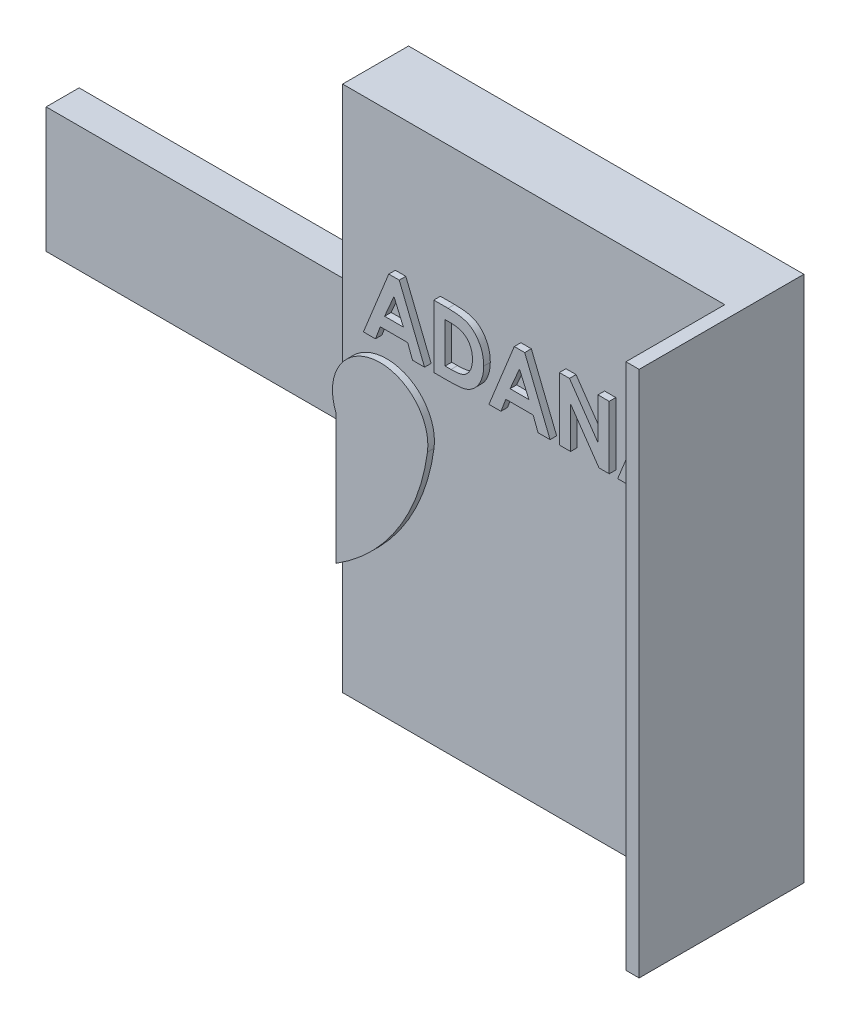
SolidWorks part; units mm, degrees
ref_plane "Ön Düzlem" through (0, 0, 0) normal (0, 0, 1) x (1, 0, 0)
ref_plane "Üst Düzlem" through (0, 0, 0) normal (0, 1, 0) x (1, 0, 0)
ref_plane "Sağ Düzlem" through (0, 0, 0) normal (1, 0, 0) x (0, 0, -1)
sketch "Çizim1" plane through (0, 0, 0) normal (0, 0, 1) x (1, 0, 0)
  line L1 (-30, 40) -> (30, 40)
  line L2 (-30, 40) -> (-30, -40)
  line L3 (-30, -40) -> (30, -40)
  line L4 (30, 40) -> (30, -40)
  line L5 (-30, 40) -> (30, -40) construction
  line L6 (-30, -40) -> (30, 40) construction
  point P0 (0, 0)
  dimension "D1" = 80
  dimension "D2" = 60
extrude "Yükseklik-Ekstrüzyon1" add sketch "Çizim1" along normal blind 10
ref_plane "Düzlem1" through (-30, 0, 0) normal (1, 0, 0) x (0, 0, -1)
sketch "Çizim2" plane through (-30, 0, 0) normal (1, 0, 0) x (0, 0, -1)
  line L0 (0, 40) -> (0, -40) construction
  line L1 (-5, 9.5) -> (0, 9.5)
  line L2 (-5, 9.5) -> (-5, -9.5)
  line L3 (-5, -9.5) -> (0, -9.5)
  line L4 (0, 9.5) -> (0, -9.5)
  line L5 (-5, 9.5) -> (0, -9.5) construction
  line L6 (-5, -9.5) -> (0, 9.5) construction
  point P0 (-2.5, 0)
  dimension "D1" = 5
  dimension "D2" = 19
extrude "Yükseklik-Ekstrüzyon2" add sketch "Çizim2" against normal blind 50
ref_plane "Düzlem2" through (30, 0, 0) normal (1, 0, 0) x (0, 0, -1)
sketch "Çizim3" plane through (30, 0, 0) normal (1, 0, 0) x (0, 0, -1)
  line L0 (-10, -40) -> (-10, 40) construction
  line L1 (-25, 40) -> (-10, 40)
  line L2 (-25, 40) -> (-25, -40)
  line L3 (-25, -40) -> (-10, -40)
  line L4 (-10, 40) -> (-10, -40)
  line L5 (-25, 40) -> (-10, -40) construction
  line L6 (-25, -40) -> (-10, 40) construction
  point P0 (-17.5, 0)
  dimension "D1" = 80
  dimension "D2" = 15
extrude "Yükseklik-Ekstrüzyon3" add sketch "Çizim3" against normal blind 2
sketch "Çizim4" plane through (0, 0, 10) normal (0, 0, 1) x (1, 0, 0)
  line L0 (28, 40) -> (-30, 40) construction
  line L1 (-30, -5.5) -> (-30, 5.5) construction
  line L2 (-30, -2.7588) -> (-30, -22.5)
  line L3 (-30, -40) -> (28, -40) construction
  arc A0 (-30, -2.7588) -> (-16.1276, -0.9405) centre (-23.3062, 0) cw
  arc A1 (-16.1276, -0.9405) -> (-30, -22.5) centre (-45.8734, 2.9565) cw
  text T0 "ADANA" font "Century Gothic" height in points 36
  dimension "D3" = 7.24
  dimension "D4" = 30
  dimension "D1" = 30
  dimension "D2" = 40
  dimension "D5" = 17.5
extrude "Yükseklik-Ekstrüzyon4" add sketch "Çizim4" along normal blind 1
